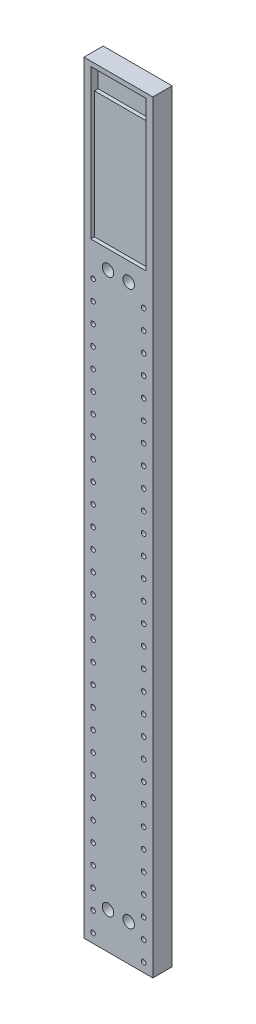
SolidWorks part; units mm, degrees
ref_plane "Front Plane" through (0, 0, 0) normal (0, 0, 1) x (1, 0, 0)
ref_plane "Top Plane" through (0, 0, 0) normal (0, 1, 0) x (1, 0, 0)
ref_plane "Right Plane" through (0, 0, 0) normal (1, 0, 0) x (0, 0, -1)
sketch "Sketch1" plane through (0, 0, 0) normal (0, 0, 1) x (1, 0, 0)
  line L1 (0, 0) -> (30, 0)
  line L2 (0, 0) -> (0, 330)
  line L3 (0, 330) -> (30, 330)
  line L4 (30, 0) -> (30, 330)
  dimension "D1" = 330
  dimension "D2" = 30
extrude "Boss-Extrude1" add sketch "Sketch1" along normal blind 8.4
sketch "Sketch2" plane through (0, 0, 8.4) normal (0, 0, 1) x (1, 0, 0)
  line L2 (0, 0) -> (30, 0) construction
  line L3 (30, 0) -> (30, 330) construction
  line L4 (10, -10.6996) -> (10, 93.9766) construction
  circle A0 centre (26, 4) radius 1
  dimension "D3" = 2
  dimension "D1" = 4
  dimension "D2" = 4
extrude "Cut-Extrude1" cut sketch "Sketch2" against normal through all
pattern_linear "LPattern1" count 30 spacing 8.5 along (0, 1, 0) of "Cut-Extrude1"
pattern_linear "LPattern2" count 2 spacing 22 along (-1, 0, 0) of "LPattern1", "Cut-Extrude1"
sketch "Sketch4" plane through (0, 0, 8.4) normal (0, 0, 1) x (1, 0, 0)
  line L0 (15, 0) -> (15, 80) construction
  line L1 (0, 0) -> (30, 0) construction
  line L3 (30, 330) -> (0, 330) construction
  line L4 (3, 265) -> (27, 265)
  line L5 (3, 265) -> (3, 330)
  line L6 (3, 330) -> (27, 330)
  line L7 (27, 265) -> (27, 330)
  line L8 (3, 265) -> (27, 330) construction
  line L9 (3, 330) -> (27, 265) construction
  point P6 (15, 297.5)
  dimension "D1" = 65
  dimension "D2" = 0
  dimension "D3" = 24
extrude "Cut-Extrude2" cut sketch "Sketch4" against normal blind 1.6
sketch "Sketch6" plane through (0, 0, 6.8) normal (0, 0, 1) x (1, 0, 0)
  line L0 (27, 265) -> (27, 330) construction
  line L1 (3, 330) -> (27, 330)
  line L2 (3, 330) -> (3, 320)
  line L3 (3, 320) -> (27, 320)
  line L4 (27, 330) -> (27, 320)
  dimension "D1" = 10
extrude "Cut-Extrude3" cut sketch "Sketch6" against normal blind 1.6
sketch "Sketch7" plane through (0, 330, 0) normal (0, 1, 0) x (1, 0, 0)
  line L0 (0, -8.4) -> (0, 0) construction
  line L1 (30, 0) -> (0, 0)
  line L2 (30, 0) -> (30, -8.4)
  line L3 (30, -8.4) -> (0, -8.4)
  line L4 (0, 0) -> (0, -8.4)
  point P7 (0, -8.3549)
  point P8 (36, -8.4)
extrude "Boss-Extrude2" add sketch "Sketch7" along normal blind 2
sketch "Sketch8" plane through (0, 0, 8.4) normal (0, 0, 1) x (1, 0, 0)
  line L0 (0, 332) -> (0, 0) construction
  line L1 (0, 0) -> (30, 0) construction
  line L2 (3, 265) -> (27, 265) construction
  line L4 (30, 0) -> (30, 332) construction
  line L5 (3, 265) -> (27, 265) construction
  circle A0 centre (10.5, 16) radius 2.5
  circle A2 centre (19.5, 257) radius 2.5
  circle A4 centre (19.5, 16) radius 2.5
  circle A5 centre (10.5, 257) radius 2.5
  point P16 (0, 0)
  point P17 (20, 250)
  point P18 (0, 0)
  dimension "D1" = 10.5
  dimension "D2" = 5
  dimension "D5" = 10.5
  dimension "D6" = 5
  dimension "D4" = 5
  dimension "D11" = 5
  dimension "D3" = 16
  dimension "D7" = 8
  dimension "D8" = 16
  dimension "D9" = 10.5
  dimension "D10" = 10.5
  dimension "D12" = 8
extrude "Cut-Extrude4" cut sketch "Sketch8" against normal through all
